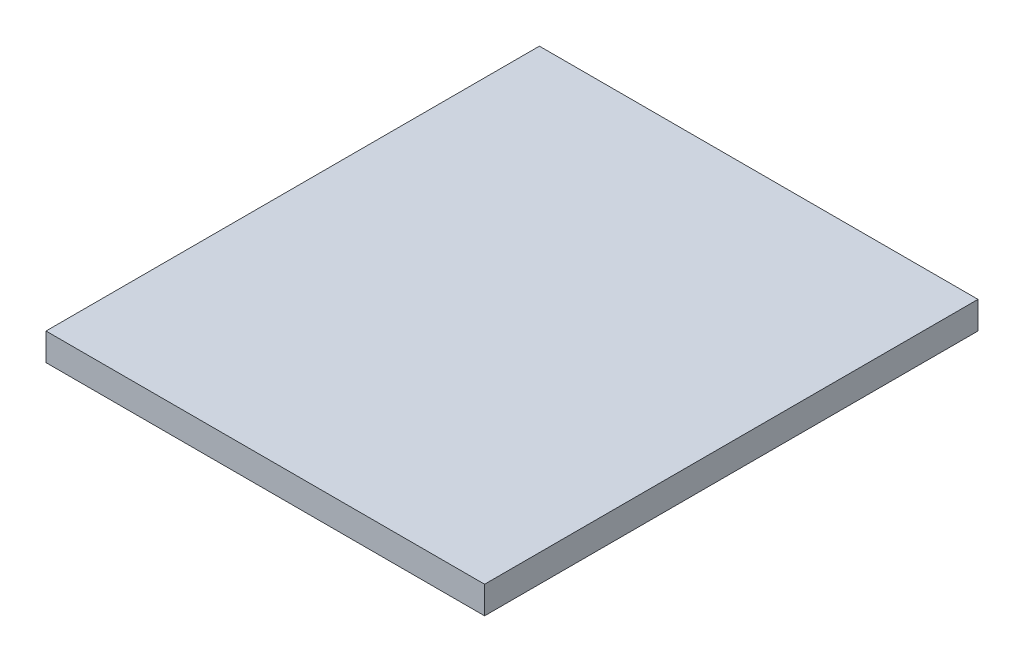
SolidWorks part; units mm, degrees
ref_plane "Front Plane" through (0, 0, 0) normal (0, 0, 1) x (1, 0, 0)
ref_plane "Top Plane" through (0, 0, 0) normal (0, 1, 0) x (1, 0, 0)
ref_plane "Right Plane" through (0, 0, 0) normal (1, 0, 0) x (0, 0, -1)
sketch "Sketch1" plane through (0, 0, 0) normal (0, 1, 0) x (1, 0, 0)
  line L1 (4, -4.5) -> (-4, -4.5)
  line L2 (4, -4.5) -> (4, 4.5)
  line L3 (4, 4.5) -> (-4, 4.5)
  line L4 (-4, -4.5) -> (-4, 4.5)
  line L5 (4, -4.5) -> (-4, 4.5) construction
  line L6 (4, 4.5) -> (-4, -4.5) construction
  point P0 (0, 0)
  dimension "D1" = 8
  dimension "D2" = 9
extrude "Boss-Extrude1" add sketch "Sketch1" along normal blind 0.5
